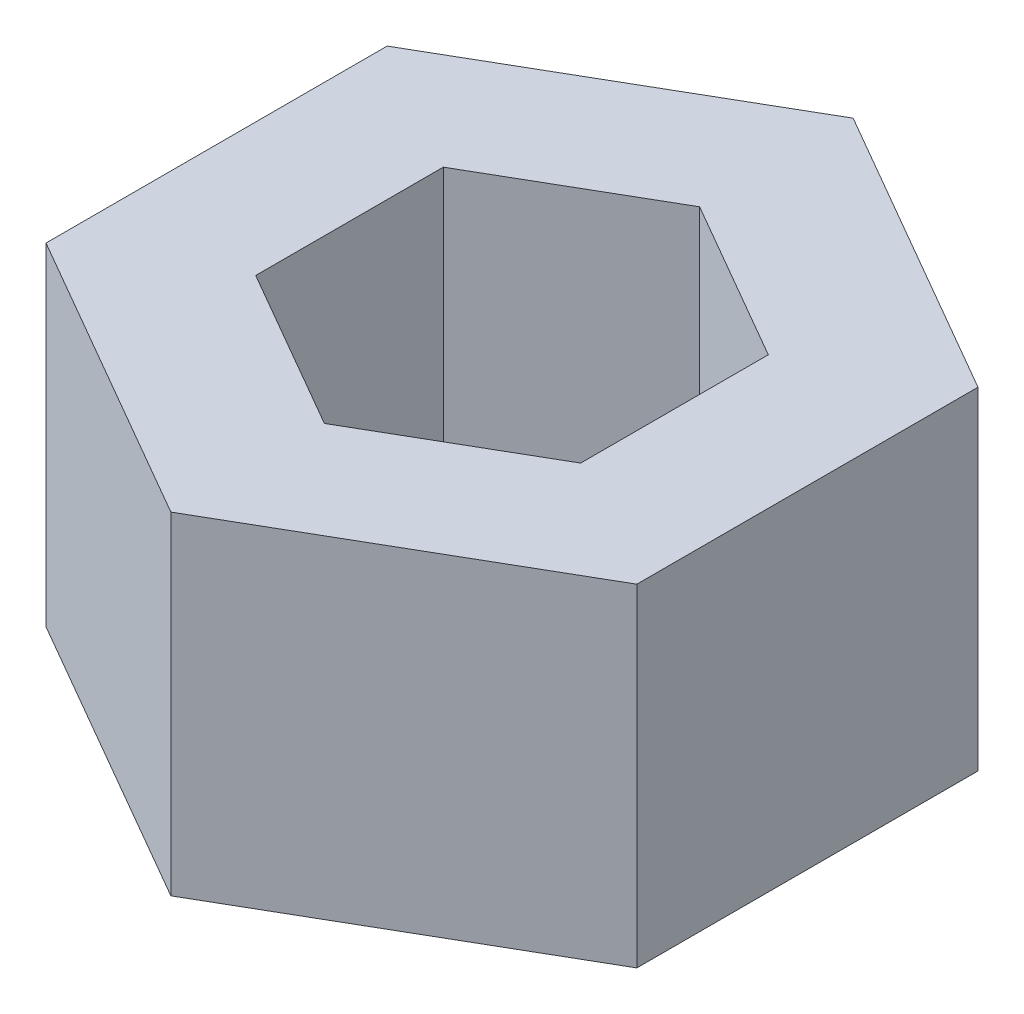
SolidWorks part; units mm, degrees
ref_plane "Front Plane" through (0, 0, 0) normal (0, 0, 1) x (1, 0, 0)
ref_plane "Top Plane" through (0, 0, 0) normal (0, 1, 0) x (1, 0, 0)
ref_plane "Right Plane" through (0, 0, 0) normal (1, 0, 0) x (0, 0, -1)
sketch "Sketch2" plane through (0, 0, 0) normal (0, 1, 0) x (1, 0, 0)
  line L1 (0, -5.0807) -> (4.4, -2.5403)
  line L2 (4.4, -2.5403) -> (4.4, 2.5403)
  line L3 (4.4, 2.5403) -> (0, 5.0807)
  line L4 (0, 5.0807) -> (-4.4, 2.5403)
  line L5 (-4.4, 2.5403) -> (-4.4, -2.5403)
  line L6 (-4.4, -2.5403) -> (0, -5.0807)
  line L7 (0, -9.2376) -> (8, -4.6188)
  line L8 (8, -4.6188) -> (8, 4.6188)
  line L9 (8, 4.6188) -> (0, 9.2376)
  line L10 (0, 9.2376) -> (-8, 4.6188)
  line L11 (-8, 4.6188) -> (-8, -4.6188)
  line L12 (-8, -4.6188) -> (0, -9.2376)
  circle A0 centre (0, 0) radius 4.4 construction
  circle A1 centre (0, 0) radius 8 construction
  dimension "D1" = 16
  dimension "D2" = 8.8
extrude "Boss-Extrude1" add sketch "Sketch2" along normal blind 9
